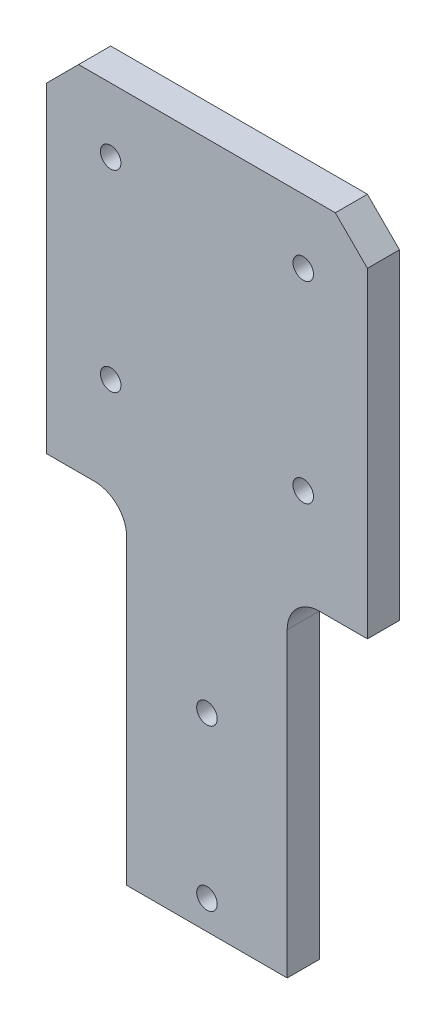
SolidWorks part; units mm, degrees
ref_plane "Front Plane" through (0, 0, 0) normal (0, 0, 1) x (1, 0, 0)
ref_plane "Top Plane" through (0, 0, 0) normal (0, 1, 0) x (1, 0, 0)
ref_plane "Right Plane" through (0, 0, 0) normal (1, 0, 0) x (0, 0, -1)
sketch "Sketch1" plane through (0, 0, 0) normal (0, 0, 1) x (1, 0, 0)
  line L0 (0, 0) -> (0, 77.8818) construction
  line L2 (-12.5, 26) -> (-12.5, -26)
  line L3 (-12.5, -26) -> (12.5, -26)
  line L4 (12.5, 26) -> (12.5, -26)
  line L5 (-12.5, 26) -> (12.5, -26) construction
  line L6 (-12.5, -26) -> (12.5, 26) construction
  line L7 (20, 81) -> (25, 76)
  line L8 (-25, 26) -> (-12.5, 26)
  line L9 (-25, 26) -> (-25, 76)
  line L10 (-20, 81) -> (20, 81)
  line L11 (25, 26) -> (25, 76)
  line L12 (-25, 76) -> (-20, 81)
  line L13 (12.5, 26) -> (25, 26)
  line L18 (-15, 41) -> (15, 71) construction
  line L19 (-15, 71) -> (15, 41) construction
  circle A0 centre (0, -21.5) radius 1.6
  circle A1 centre (0, 3.5) radius 1.6
  circle A2 centre (-15, 71) radius 1.6
  circle A3 centre (15, 71) radius 1.6
  circle A4 centre (-15, 41) radius 1.6
  circle A5 centre (15, 41) radius 1.6
  point P0 (0, 0)
  point P9 (25, 81)
  point P10 (-25, 81)
  point P20 (0, 56)
  dimension "D5" = 22.5
  dimension "D1" = 52
  dimension "D2" = 25
  dimension "D3" = 50
  dimension "D4" = 55
  dimension "D6" = 25
  dimension "D7" = 30
  dimension "D8" = 30
extrude "Boss-Extrude1" add sketch "Sketch1" along normal blind 5
fillet "Fillet1" radius 5 2 edges at (-12.5, 26, 2.5) (12.5, 26, 2.5)
